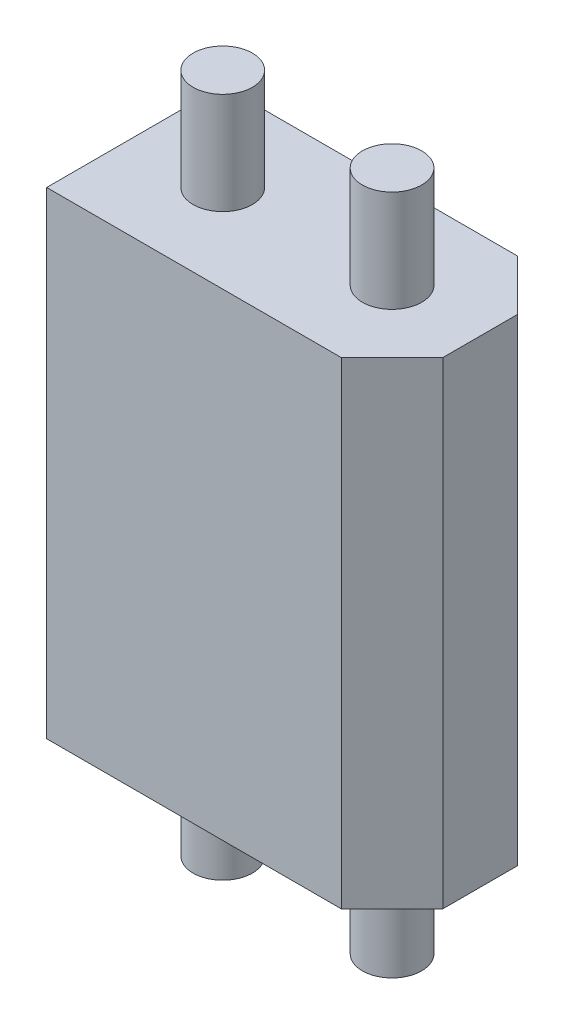
SolidWorks part; units mm, degrees
ref_plane "Front Plane" through (0, 0, 0) normal (0, 0, 1) x (1, 0, 0)
ref_plane "Top Plane" through (0, 0, 0) normal (0, 1, 0) x (1, 0, 0)
ref_plane "Right Plane" through (0, 0, 0) normal (1, 0, 0) x (0, 0, -1)
sketch "Sketch1" plane through (0, 0, 0) normal (0, 1, 0) x (1, 0, 0)
  line L1 (-5.1, -2.6) -> (5.1, -2.6)
  line L2 (-5.1, -2.6) -> (-5.1, 2.6)
  line L3 (-5.1, 2.6) -> (5.1, 2.6)
  line L4 (5.1, -2.6) -> (5.1, 2.6)
  line L5 (-5.1, -2.6) -> (5.1, 2.6) construction
  line L6 (-5.1, 2.6) -> (5.1, -2.6) construction
  point P0 (0, 0)
  dimension "D1" = 10.2
  dimension "D2" = 5.2
extrude "Boss-Extrude1" add sketch "Sketch1" along normal mid plane 14.1
chamfer "Chamfer1" distance 1.5 angle 45 2 edges at (5.1, 0, -2.6) (5.1, 0, 2.6)
sketch "Sketch2" plane through (0, 0, 0) normal (0, 1, 0) x (1, 0, 0)
  line L0 (-2.5, 0) -> (2.5, 0) construction
  circle A0 centre (-2.5, 0) radius 0.875
  circle A1 centre (2.5, 0) radius 0.875
  point P4 (0, 0)
  dimension "D2" = 1.75
  dimension "D3" = 1.75
  dimension "D1" = 5
extrude "Boss-Extrude2" add sketch "Sketch2" along normal offset from surface 3 and the other way offset from surface (10.05 mm away) 3 up to face at (1.2, 7.05, 0) offset beyond the face yes other way up to face at (1.2, -7.05, 0)
